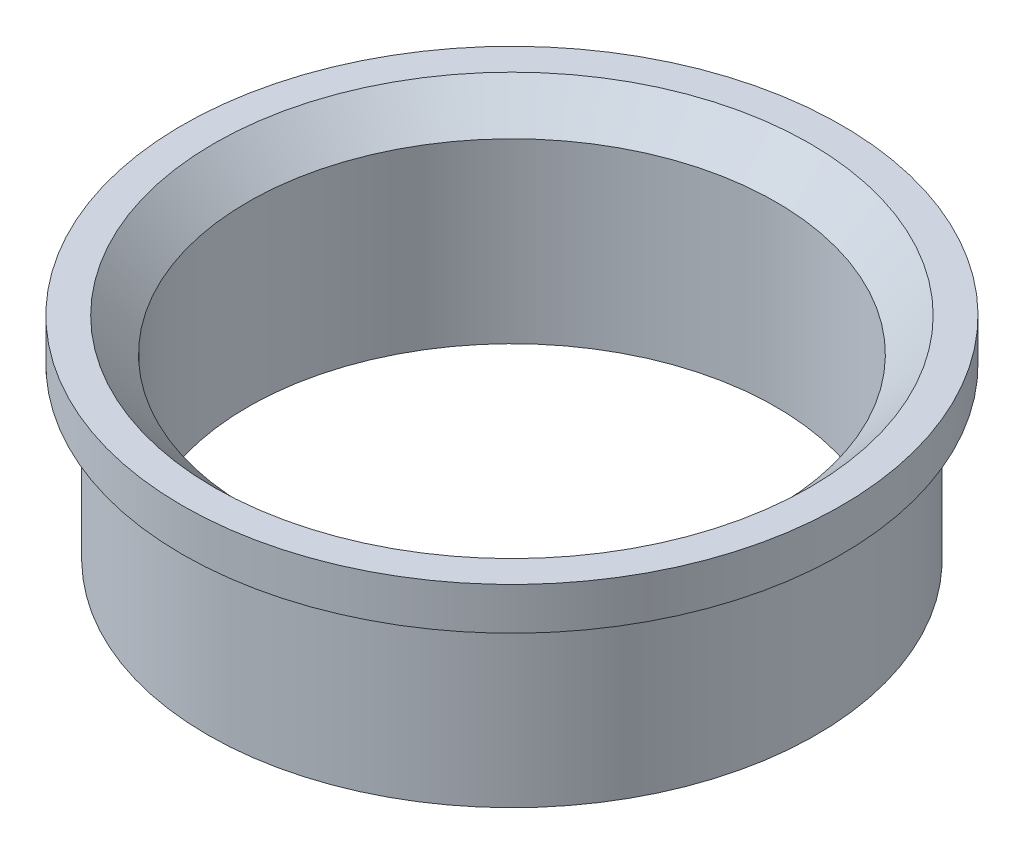
SolidWorks part; units mm, degrees
ref_plane "Front Plane" through (0, 0, 0) normal (0, 0, 1) x (1, 0, 0)
ref_plane "Top Plane" through (0, 0, 0) normal (0, 1, 0) x (1, 0, 0)
ref_plane "Right Plane" through (0, 0, 0) normal (1, 0, 0) x (0, 0, -1)
sketch "Sketch2" plane through (0, 0, 0) normal (0, 0, 1) x (1, 0, 0)
  line L0 (0, 72.7881) -> (0, -77.2174) construction
  line L1 (-89.4274, 0) -> (116.092, 0) construction
  line L2 (62.5, 0) -> (62.5, 42)
  line L3 (62.5, 42) -> (70.5, 50)
  line L4 (70.5, 50) -> (78, 50)
  line L5 (78, 50) -> (78, 40)
  line L6 (78, 40) -> (72, 40)
  line L7 (72, 40) -> (72, 0)
  line L8 (72, 0) -> (62.5, 0)
  dimension "D1" = 78
  dimension "D2" = 72
  dimension "D3" = 62.5
  dimension "D4" = 40
  dimension "D5" = 10
  dimension "D6" = 8
  dimension "D7" = 135
revolve "Revolve1" add sketch "Sketch2" angle 360 about L0
